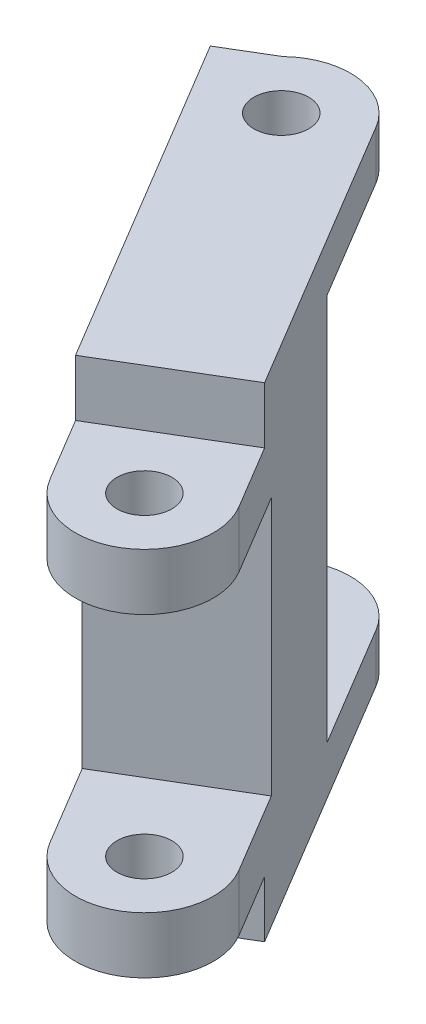
SolidWorks part; units mm, degrees
material "Plain Carbon Steel"
ref_plane "Front Plane" through (0, 0, 0) normal (0, 0, 1) x (1, 0, 0)
ref_plane "Top Plane" through (0, 0, 0) normal (0, 1, 0) x (1, 0, 0)
ref_plane "Right Plane" through (0, 0, 0) normal (1, 0, 0) x (0, 0, -1)
sketch "Sketch1" plane through (0, 0, 0) normal (0, 1, 0) x (1, 0, 0)
  line L0 (47.2297, 219.0186) -> (732.563, 219.0186) construction
  line L1 (0.5473, 46.7734) -> (-12.0963, 67.9168)
  line L2 (-6.7841, 42.3892) -> (-21.5701, 67.1151)
  line L3 (-21.5701, 67.1151) -> (-18.7462, 68.8038)
  circle A0 centre (-3.1184, 44.5813) radius 1.7
  arc A1 (-6.7841, 42.3892) -> (0.5473, 46.7734) centre (-3.1184, 44.5813) ccw
  circle A2 centre (-15.7738, 65.7176) radius 1.7
  arc A3 (-19.676, 63.9476) -> (-19.1796, 63.1175) centre (-15.7738, 65.7176) ccw
  arc A4 (-12.0963, 67.9168) -> (-18.7462, 68.8038) centre (-15.7738, 65.7176) ccw
extrude "Boss-Extrude1" add sketch "Sketch1" along normal blind 30 contours L1 A4 L3 L2 A1 A0 A2
sketch "Sketch2" plane through (13.6744, 0, -8.1772) normal (-0.8583, 0, 0.5132) x (0.5132, 0, 0.8583)
  line L0 (-68.6721, 30) -> (-68.6721, 0) construction
  line L1 (-68.6721, 3) -> (-55.6721, 3)
  line L2 (-68.6721, 30) -> (-68.6721, 0) construction
  line L3 (-68.6721, 27) -> (-55.6721, 27)
  line L4 (-55.6721, 3) -> (-55.6721, 27)
  line L5 (-39.8624, 30) -> (-68.6721, 30) construction
  line L6 (-39.8624, 0) -> (-68.6721, 0) construction
  line L8 (-55.6721, 27) -> (-75.8056, 27)
  line L9 (-55.6721, 27) -> (-55.6721, 3)
  line L10 (-55.6721, 3) -> (-75.8056, 3)
  line L11 (-75.8056, 27) -> (-75.8056, 3)
  line M8 (-68.6721, 30) -> (-68.6721, 0)
  dimension "D1" = 3
  dimension "D2" = 3
  dimension "D3" = 13
extrude "Cut-Extrude2" cut sketch "Sketch2" against normal blind 30 contours L1 L4 L3 M8 | L8 L11 L10 M8
sketch "Sketch3" plane through (13.6744, 0, -8.1772) normal (-0.8583, 0, 0.5132) x (0.5132, 0, 0.8583)
  line L0 (-55.6721, 3) -> (-55.6721, 27) construction
  line L1 (-45.6721, 7) -> (-29.2785, 7)
  line L2 (-45.6721, 7) -> (-45.6721, 23)
  line L3 (-45.6721, 23) -> (-29.2785, 23)
  line L4 (-29.2785, 7) -> (-29.2785, 23)
  line L5 (-39.8624, 0) -> (-68.6721, 0) construction
  line L6 (-39.8624, 30) -> (-68.6721, 30) construction
  dimension "D1" = 10
  dimension "D2" = 7
  dimension "D3" = 7
extrude "Cut-Extrude3" cut sketch "Sketch3" against normal blind 30
sketch "Sketch5" plane through (0, 0, 0) normal (0, 1, 0) x (1, 0, 0)
  line L0 (-1.4174, 50.9289) -> (-10.2093, 46.073)
  line L1 (-10.2093, 46.073) -> (-5.8134, 38.1137)
  line L2 (-5.8134, 38.1137) -> (3.9724, 43.5184)
  line L3 (3.7771, 43.4105) -> (-1.4174, 50.9289)
sketch "Sketch7" plane through (0, 0, 0) normal (0, -1, 0) x (-1, 0, 0)
  line L0 (1.8178, 50.7284) -> (9.1492, 46.3442)
  line L1 (-0.5473, 46.7734) -> (12.0963, 67.9168) construction
  line L2 (6.7841, 42.3892) -> (21.5701, 67.1151) construction
  line L3 (9.1492, 46.3442) -> (4.2106, 38.0856)
  line L4 (4.2106, 38.0856) -> (-3.391, 42.018)
  line L5 (-3.391, 42.018) -> (1.8178, 50.7284)
extrude "Cut-Extrude4" cut sketch "Sketch7" against normal blind 3.5
sketch "Sketch9" plane through (13.6744, 0, -8.1772) normal (-0.8583, 0, 0.5132) x (0.5132, 0, 0.8583)
  line L0 (-44.4707, 30) -> (-44.4707, 26.5)
  line L1 (-39.8624, 30) -> (-68.6721, 30) construction
  line L2 (-44.4707, 26.5) -> (-33.4167, 26.5)
  line L3 (-33.4167, 26.5) -> (-33.4167, 30.5449)
  line L4 (-33.4167, 30.5449) -> (-44.4707, 30.5449)
  line L5 (-44.4707, 30) -> (-44.4707, 30.5449)
  line L6 (-44.4707, 3.5) -> (-44.4707, 0) construction
  dimension "D1" = 0
  dimension "D2" = 3.5
extrude "Cut-Extrude5" cut sketch "Sketch9" against normal through all
